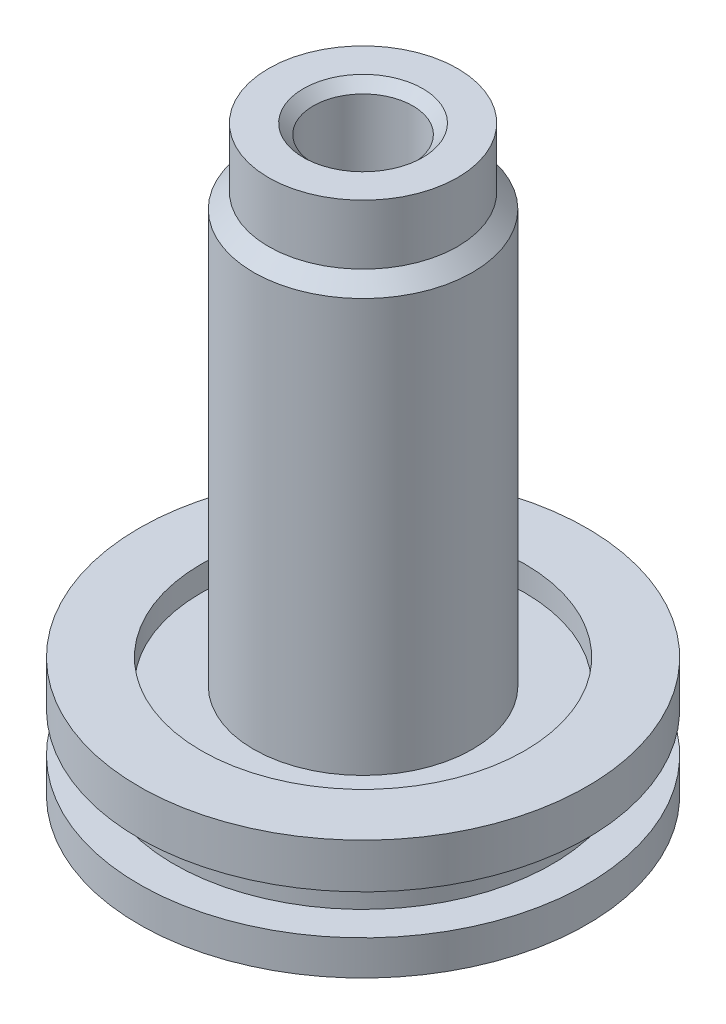
SolidWorks part; units mm, degrees
material "1.0726 (35S20)"
ref_plane "Спереди" through (0, 0, 0) normal (0, 0, 1) x (1, 0, 0)
ref_plane "Сверху" through (0, 0, 0) normal (0, 1, 0) x (1, 0, 0)
ref_plane "Справа" through (0, 0, 0) normal (1, 0, 0) x (0, 0, -1)
ref_plane "Плоскость4" through (0, 0, 0) normal (0, 0, -1) x (-1, 0, 0)
sketch "Эскиз1" plane through (0, 0, 0) normal (0, 0, -1) x (-1, 0, 0)
  line L0 (-22, 0) -> (0, 0)
  line L1 (0, 0) -> (0, 20.0718)
  line L2 (0, 20.0718) -> (-12, 27)
  line L3 (-12, 27) -> (-12, 59)
  line L4 (-12, 59) -> (-10, 59)
  line L5 (-10, 59) -> (-10, 123)
  line L6 (-10, 123) -> (-12, 125)
  line L7 (-12, 125) -> (-19, 125)
  line L8 (-19, 125) -> (-19, 113)
  line L9 (-19, 113) -> (-22, 110)
  line L10 (-22, 110) -> (-22, 27)
  line L11 (-22, 27) -> (-32.5, 27)
  line L12 (-32.5, 27) -> (-32.5, 32)
  line L13 (-32.5, 32) -> (-45, 32)
  line L14 (-45, 32) -> (-45, 23)
  line L15 (-45, 23) -> (-38, 23)
  line L16 (-38, 23) -> (-38, 15)
  line L17 (-38, 15) -> (-45, 15)
  line L18 (-45, 15) -> (-45, 8)
  line L19 (-45, 8) -> (-22, 8)
  line L20 (-22, 8) -> (-22, 0)
  line L21 (0, 0) -> (0, 125) construction
revolve "Повернуть1" add sketch "Эскиз1" angle 360 about L21
